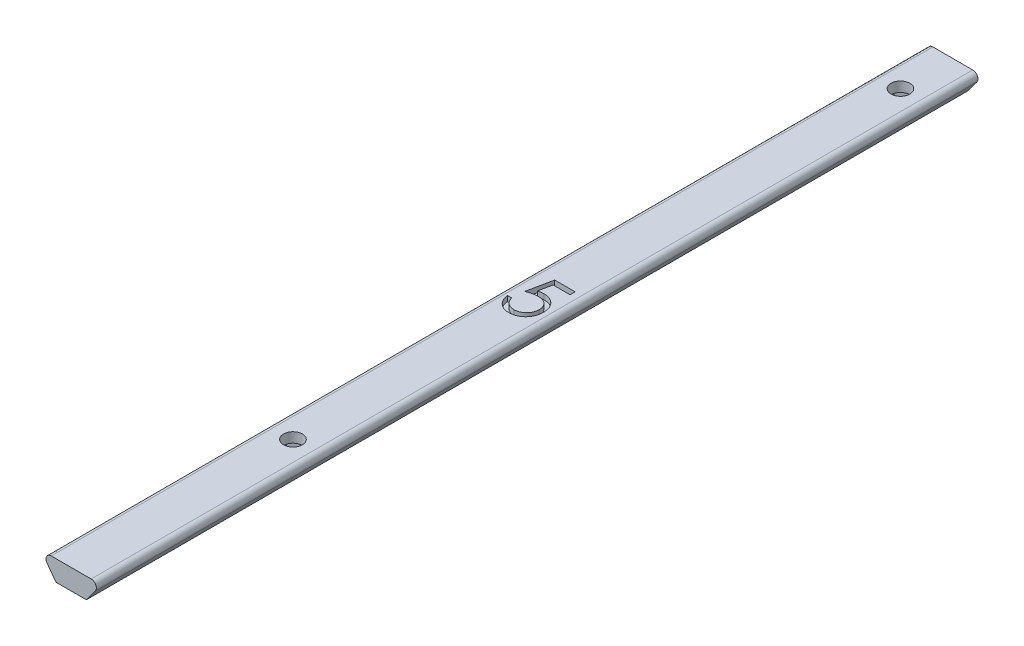
SolidWorks part; units mm, degrees
ref_plane "Front Plane" through (0, 0, 0) normal (0, 0, 1) x (1, 0, 0)
ref_plane "Top Plane" through (0, 0, 0) normal (0, 1, 0) x (1, 0, 0)
ref_plane "Right Plane" through (0, 0, 0) normal (1, 0, 0) x (0, 0, -1)
sketch "Sketch1" plane through (0, 0, 0) normal (0, 0, 1) x (1, 0, 0)
  line L0 (0, 0) -> (5.8, 0)
  line L1 (-2.9, 3.9) -> (8.7, 3.9)
  line L2 (0, 0) -> (-2.9, 3.9)
  line L3 (5.8, 0) -> (8.7, 3.9)
  dimension "D1" = 11.6
  dimension "D2" = 3.9
  dimension "D3" = 5.8
  dimension "D4" = 2.9
extrude "Boss-Extrude1" add sketch "Sketch1" along normal blind 168.35
fillet "Fillet1" radius 1 2 edges at (-2.9, 3.9, 84.175) (8.7, 3.9, 84.175)
sketch "Sketch2" plane through (0, 0, 0) normal (0, -1, 0) x (1, 0, 0)
  line L0 (2.9, 168.35) -> (2.9, 126) construction
  line L1 (0, 168.35) -> (5.8, 168.35) construction
  circle A0 centre (2.9, 126) radius 1.8
  dimension "D2" = 3.6
  dimension "D1" = 42.35
extrude "Cut-Extrude1" cut sketch "Sketch2" against normal blind 200
sketch "Sketch3" plane through (0, 0, 0) normal (0, -1, 0) x (1, 0, 0)
  line L1 (2.9023, 122.6514) -> (5.8011, 124.3276)
  line L2 (5.8011, 124.3276) -> (5.7989, 127.6763)
  line L3 (5.7989, 127.6763) -> (2.8977, 129.3486)
  line L4 (2.8977, 129.3486) -> (-0.0011, 127.6724)
  line L5 (-0.0011, 127.6724) -> (0.0011, 124.3237)
  line L6 (0.0011, 124.3237) -> (2.9023, 122.6514)
  circle A0 centre (2.9, 126) radius 2.9 construction
  dimension "D1" = 5.8
extrude "Cut-Extrude2" cut sketch "Sketch3" against normal blind 2
pattern_linear "LPattern1" count 3 spacing 116 along (0, 0, -1) of "Cut-Extrude1", "Cut-Extrude2"
sketch "Sketch4" plane through (0, 3.9, 0) normal (0, 1, 0) x (1, 0, 0)
  line L0 (-0.9102, -84.175) -> (0.0898, -84.175) construction
  line L3 (-0.9102, 0) -> (-0.9102, -168.35) construction
  text T0 "5\r\n" font "Century Gothic" height in points 36
  dimension "D1" = 1
extrude "Cut-Extrude3" cut sketch "Sketch4" against normal blind 1
